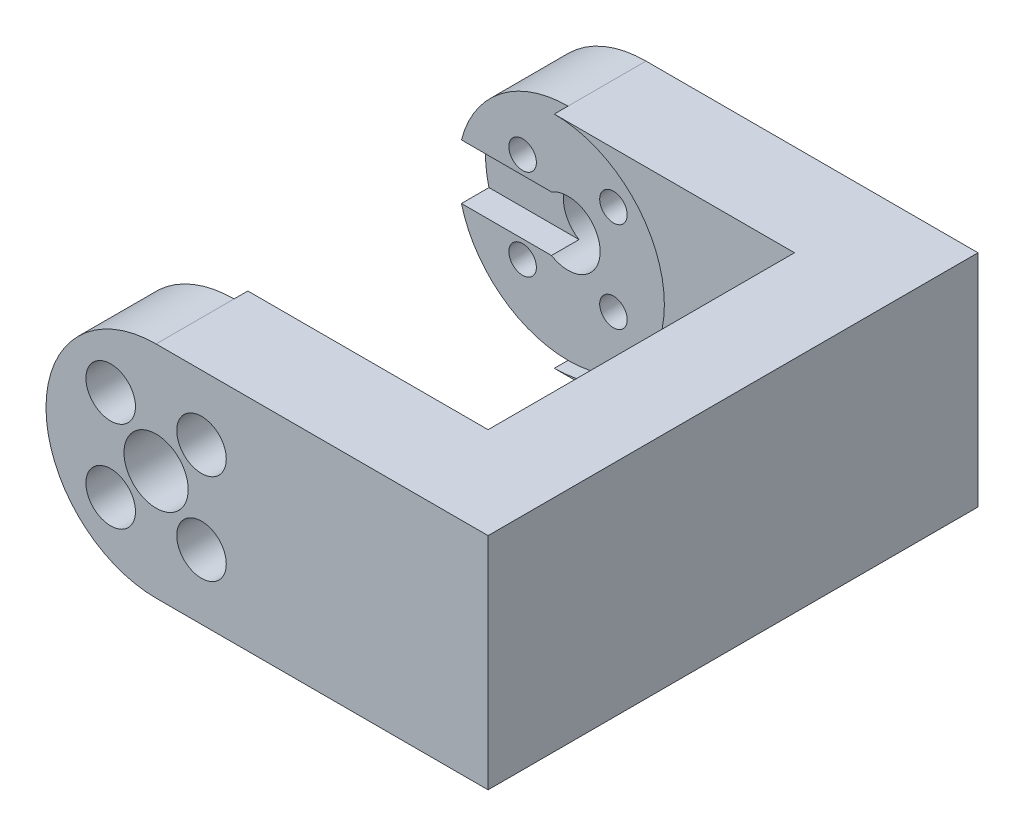
SolidWorks part; units mm, degrees
ref_plane "前视基准面" through (0, 0, 0) normal (0, 0, 1) x (1, 0, 0)
ref_plane "上视基准面" through (0, 0, 0) normal (0, 1, 0) x (1, 0, 0)
ref_plane "右视基准面" through (0, 0, 0) normal (1, 0, 0) x (0, 0, -1)
other "Configuration Table"
sketch "草图1" plane through (0, 0, 0) normal (0, 0, 1) x (1, 0, 0)
  line L0 (0, 12) -> (36.1853, 12)
  line L1 (36.1853, 12) -> (36.1853, -12)
  line L2 (36.1853, -12) -> (0, -12)
  arc A0 (0, 12) -> (0, -12) centre (0, 0) ccw
  dimension "D1" = 36.1853
extrude "凸台-拉伸1" add sketch "草图1" along normal blind 13.5
ref_plane "基准面1" through (0, 0, -16.7) normal (0, 0, -1) x (-1, 0, 0)
sketch "草图5" plane through (0, 0, 0) normal (0, 0, -1) x (-1, 0, 0)
  circle A0 centre (0, 0) radius 10.1
extrude "切除-拉伸2" cut sketch "草图5" against normal blind 1.5
sketch "草图7" plane through (0, 0, 1.5) normal (0, 0, -1) x (-1, 0, 0)
  circle A0 centre (0, 0) radius 3.5
extrude "切除-拉伸3" cut sketch "草图7" against normal blind 37
sketch "草图9" plane through (0, 0, 1.5) normal (0, 0, -1) x (-1, 0, 0)
  line L0 (-4.9497, 4.9497) -> (0, 0) construction
  line L1 (0, 0) -> (0, 7.7766) construction
  circle A0 centre (-4.9497, 4.9497) radius 1.5
  circle A1 centre (4.9497, 4.9497) radius 1.5
  circle A2 centre (4.9497, -4.9497) radius 1.5
  circle A3 centre (-4.9497, -4.9497) radius 1.5
  point P14 (0, 0)
  dimension "D1" = 7
  dimension "D2" = 45
  dimension "D3" = 4
extrude "切除-拉伸4" cut sketch "草图9" against normal blind 24.5
mirror "镜向14" about plane through (0, 0, -16.7) normal (0, 0, -1) of bodies 111
sketch "草图11" plane through (36.1853, 0, 0) normal (1, 0, 0) x (0, 0, -1)
  line L1 (-13.5, 12) -> (46.9, 12)
  line L2 (-13.5, 12) -> (-13.5, -12)
  line L3 (-13.5, -12) -> (46.9, -12)
  line L4 (46.9, 12) -> (46.9, -12)
extrude "凸台-拉伸2" add sketch "草图11" against normal blind 10
sketch "草图12" plane through (0, 0, 13.5) normal (0, 0, 1) x (1, 0, 0)
  circle A0 centre (4.9497, 4.9497) radius 2.7
  circle A1 centre (4.9497, -4.9497) radius 2.7
  circle A2 centre (-4.9497, -4.9497) radius 2.7
  circle A3 centre (-4.9497, 4.9497) radius 2.7
  point P12 (0, 0)
  dimension "D1" = 4
extrude "切除-拉伸5" cut sketch "草图12" against normal blind 8.5
sketch "草图18" plane through (0, 0, 0) normal (0, 0, -1) x (-1, 0, 0)
  circle A0 centre (0, 0) radius 12
extrude "切除-拉伸9" cut sketch "草图18" against normal blind 1.5
sketch "草图19" plane through (0, 0, 1.5) normal (0, 0, -1) x (-1, 0, 0)
  line L4 (0, 0) -> (7.3362, 0) construction
  line L5 (14.6724, -3) -> (0, -3)
  line L6 (14.6724, -3) -> (14.6724, 3)
  line L7 (14.6724, 3) -> (0, 3)
  line L8 (0, -3) -> (0, 3)
  line L9 (14.6724, -3) -> (0, 3) construction
  line L10 (14.6724, 3) -> (0, -3) construction
  point P0 (7.3362, 0)
  dimension "D1" = 6
extrude "切除-拉伸10" cut sketch "草图19" against normal blind 3
sketch "草图20" plane through (0, 0, 13.5) normal (0, 0, 1) x (1, 0, 0)
  line L1 (-17.9701, 18.7991) -> (58.5374, 18.7991)
  line L2 (-17.9701, 18.7991) -> (-17.9701, -18.303)
  line L3 (-17.9701, -18.303) -> (58.5374, -18.303)
  line L4 (58.5374, 18.7991) -> (58.5374, -18.303)
extrude "切除-拉伸11" cut sketch "草图20" against normal blind 3.5
mirror "镜向24" about plane through (0, 0, -16.7) normal (0, 0, -1) of "切除-拉伸5", "切除-拉伸9", "切除-拉伸10"
mirror "镜向26" about plane through (0, 0, -16.7) normal (0, 0, -1) of "切除-拉伸11"
